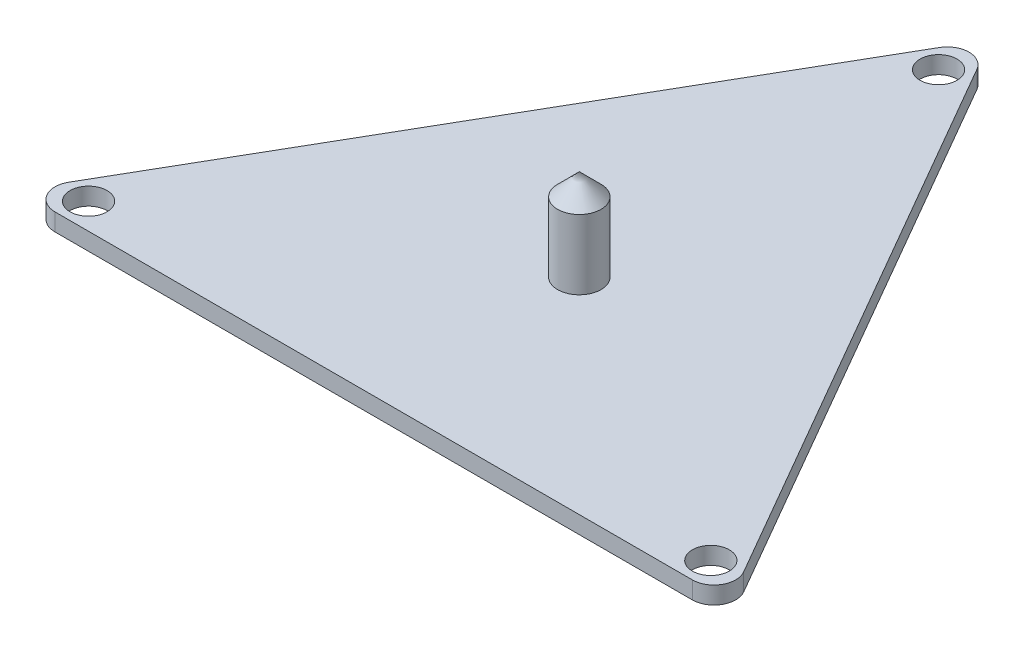
SolidWorks part; units mm, degrees
ref_plane "Front Plane" through (0, 0, 0) normal (0, 0, 1) x (1, 0, 0)
ref_plane "Top Plane" through (0, 0, 0) normal (0, 1, 0) x (1, 0, 0)
ref_plane "Right Plane" through (0, 0, 0) normal (1, 0, 0) x (0, 0, -1)
sketch "Sketch1" plane through (0, 0, 0) normal (0, 1, 0) x (1, 0, 0)
  line L0 (-781.4563, -263.8735) -> (-65.6863, 975.8765)
  line L1 (-65.6863, 975.8765) -> (650.0837, -263.8735)
  line L2 (650.0837, -263.8735) -> (-781.4563, -263.8735)
  line L3 (-65.6863, 1095.8765) -> (754.0068, -323.8735)
  line L4 (754.0068, -323.8735) -> (-885.3793, -323.8735)
  line L5 (-885.3793, -323.8735) -> (-65.6863, 1095.8765)
  line L6 (-65.6863, 975.8765) -> (-65.6863, -263.8735) construction
  line L7 (292.1987, 356.0015) -> (-781.4563, -263.8735) construction
  point P8 (-65.6863, 149.3765)
  dimension "D1" = 826.5
  dimension "D2" = 60
extrude "Boss-Extrude1" add sketch "Sketch1" along normal blind 40 contours L3 L4 L5
sketch "Sketch4" plane through (0, 40, 0) normal (0, 1, 0) x (1, 0, 0)
  line L6 (-65.6863, 975.8765) -> (-781.4563, -263.8735)
  line L7 (-781.4563, -263.8735) -> (650.0837, -263.8735)
  line L8 (650.0837, -263.8735) -> (-65.6863, 975.8765)
  line L9 (-65.6863, 975.8765) -> (-781.4563, -263.8735)
  line L10 (-781.4563, -263.8735) -> (650.0837, -263.8735)
  line L11 (650.0837, -263.8735) -> (-65.6863, 975.8765)
  dimension "D1" = 60
hole_wizard "Ø1.0 (1) Diameter Hole1" positions "Sketch5" profile "Sketch7" hole size "Ø1.0" standard "ISO" end condition through all
sketch "Sketch5" plane through (0, 40, 0) normal (0, 1, 0) x (1, 0, 0)
  point P0 (-65.6863, 975.8765)
  point P3 (-781.4563, -263.8735)
  point P6 (650.0837, -263.8735)
sketch "Sketch7" plane through (-65.6863, 40, -975.8765) normal (1, 0, 0) x (0, 0, 1)
  line L0 (0, 0) -> (0, 40)
  line L1 (0, 40) -> (42.5, 40)
  line L2 (42.5, 40) -> (42.5, 0)
  line L5 (42.5, 0) -> (0, 0)
  line L11 (0, -6.35) -> (0, 107.95) construction
  dimension "Thru Hole Dia." = 85
  dimension "Thru Hole Depth" = 40
sketch "Sketch8" plane through (0, 0, 0) normal (0, -1, 0) x (-1, 0, 0)
  circle A0 centre (65.6863, 149.3765) radius 946.5 construction
  circle A1 centre (65.6863, 149.3765) radius 50
  dimension "D1" = 100
extrude "Boss-Extrude2" add sketch "Sketch8" against normal blind 250
fillet "Fillet1" radius 50 3 edges at (754.0068, 20, 323.8735) (-885.3793, 20, 323.8735) (-65.6863, 20, -1095.8765)
chamfer "Chamfer1" distance 50 angle 45 1 edges at (-65.6863, 250, -199.3765)
equation "\"TRIANGLE_OFFSET\"= 60"
equation "\"D2@Sketch1\"=\"TRIANGLE_OFFSET\""
equation "\"TRIANGLE_Z\"= 40"
equation "\"D1@Boss-Extrude1\"=\"TRIANGLE_Z\""
equation "\"D1@Sketch4\"=\"TRIANGLE_OFFSET\""
equation "\"d\"=826.5"
equation "\"D1@Sketch1\"=\"d\""
